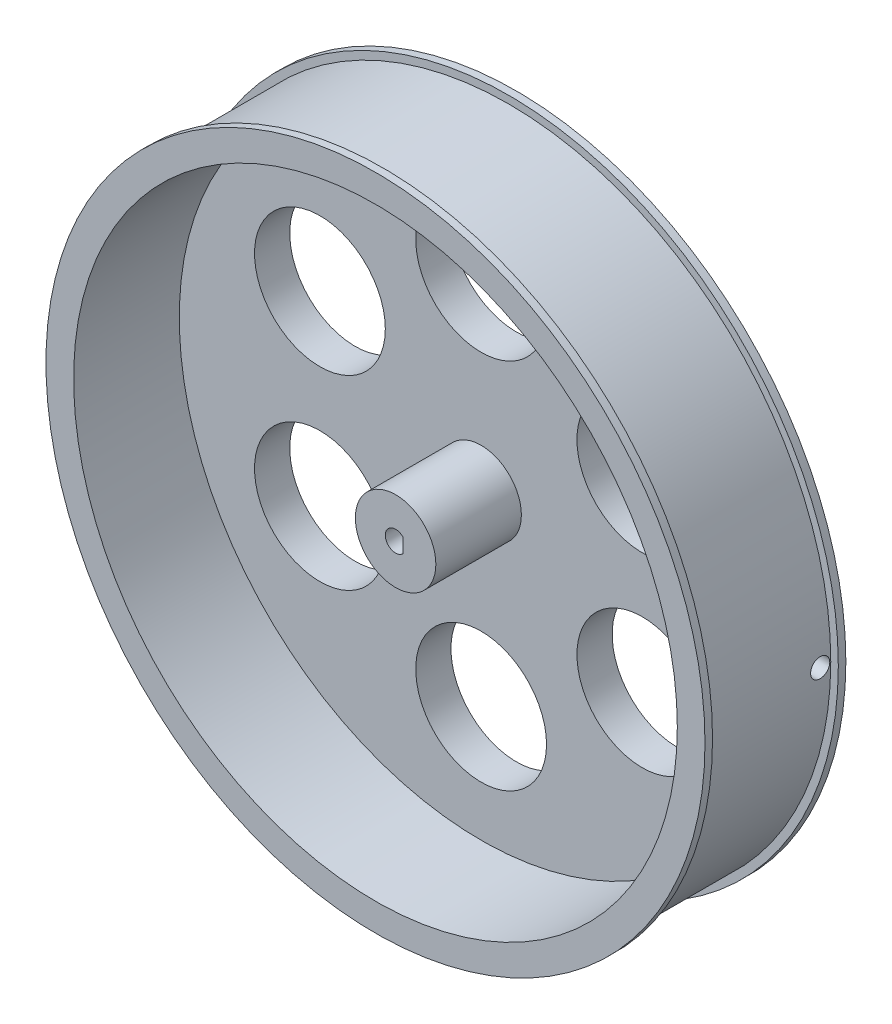
SolidWorks part; units mm, degrees
ref_plane "Front Plane" through (0, 0, 0) normal (0, 0, 1) x (1, 0, 0)
ref_plane "Top Plane" through (0, 0, 0) normal (0, 1, 0) x (1, 0, 0)
ref_plane "Right Plane" through (0, 0, 0) normal (1, 0, 0) x (0, 0, -1)
sketch "Sketch1" plane through (0, 0, 0) normal (0, 0, 1) x (1, 0, 0)
  circle A0 centre (0, 0) radius 64
  circle A1 centre (0, 0) radius 60
extrude "Rim" add sketch "Sketch1" along normal blind 28
sketch "Sketch2" plane through (0, 0, 0) normal (0, 0, 1) x (1, 0, 0)
  circle A0 centre (0, 0) radius 65.5
  circle A1 centre (0, 0) radius 63
extrude "Inner_bead_lip" add sketch "Sketch2" along normal blind 1.5
ref_plane "P_Front_26p5" through (0, 0, 26.5) normal (0, 0, 1) x (1, 0, 0)
sketch "Sketch3" plane through (0, 0, 26.5) normal (0, 0, 1) x (1, 0, 0)
  circle A0 centre (0, 0) radius 65.5
  circle A1 centre (0, 0) radius 63
extrude "Outer_bead_lip" add sketch "Sketch3" along normal blind 1.5
sketch "Sketch4" plane through (0, 0, 0) normal (0, 0, 1) x (1, 0, 0)
  circle A0 centre (0, 0) radius 61
extrude "Web" add sketch "Sketch4" along normal blind 7
sketch "Sketch5" plane through (0, 0, 0) normal (0, 0, 1) x (1, 0, 0)
  circle A0 centre (0, 0) radius 8
extrude "Hub_boss" add sketch "Sketch5" along normal blind 24
ref_plane "P_Front_m1" through (0, 0, -1) normal (0, 0, 1) x (1, 0, 0)
sketch "Sketch6" plane through (0, 0, -1) normal (0, 0, 1) x (1, 0, 0)
  circle A0 centre (32.0429, 18.5) radius 13
  circle A1 centre (0, 37) radius 13
  circle A2 centre (-32.0429, 18.5) radius 13
  circle A3 centre (-32.0429, -18.5) radius 13
  circle A4 centre (0, -37) radius 13
  circle A5 centre (32.0429, -18.5) radius 13
extrude "Lightening_holes" cut sketch "Sketch6" along normal blind 9
sketch "Sketch7" plane through (0, 0, -1) normal (0, 0, 1) x (1, 0, 0)
  line L0 (1.5, -1.3973) -> (1.5, 1.3973)
  arc A0 (1.5, 1.3973) -> (1.5, -1.3973) centre (0, 0) ccw
extrude "D_bore_4mm" cut sketch "Sketch7" along normal blind 30
sketch "Sketch8" plane through (0, 0, 0) normal (1, 0, 0) x (0, 0, -1)
  circle A0 centre (-3.6, 0) radius 1.3
extrude "Grub_screw_M3" cut sketch "Sketch8" along normal blind 9
ref_plane "P_Right_8p5" through (8.5, 0, 0) normal (1, 0, 0) x (0, 0, -1)
sketch "Sketch9" plane through (8.5, 0, 0) normal (1, 0, 0) x (0, 0, -1)
  circle A0 centre (-3.6, 0) radius 1.9
extrude "Grub_key_access" cut sketch "Sketch9" along normal blind 57.5
